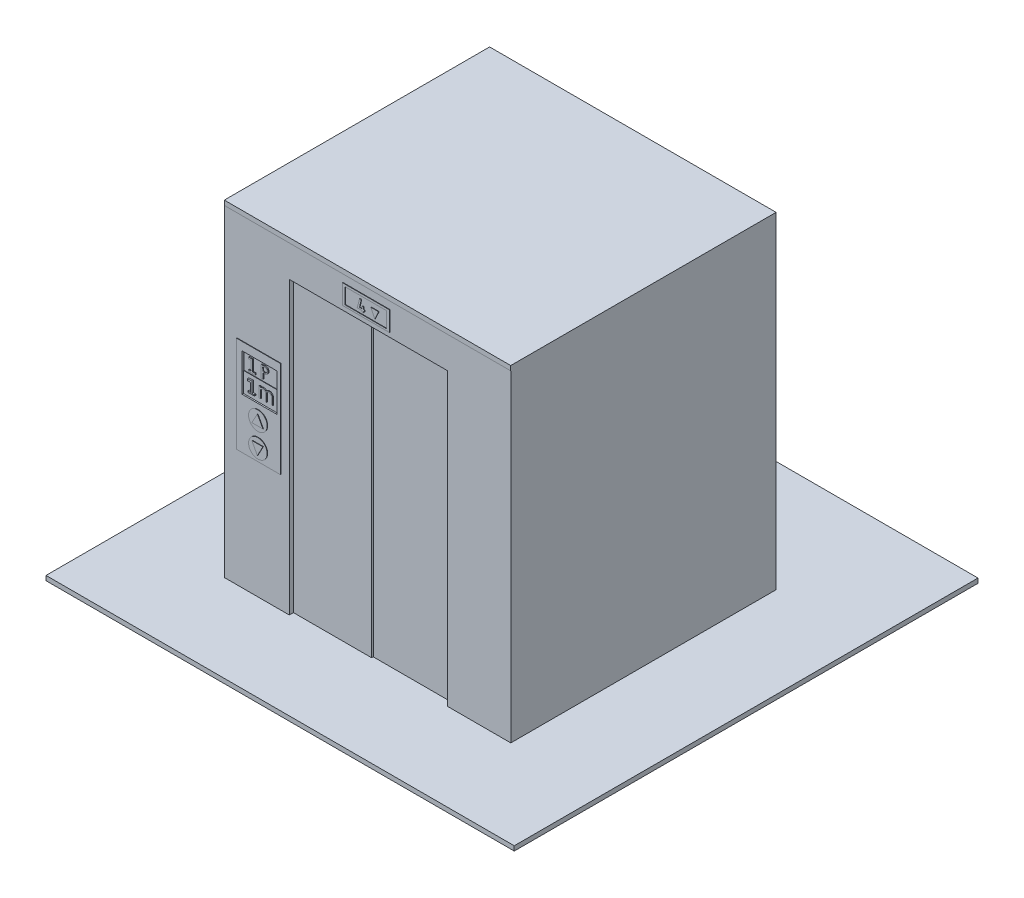
SolidWorks part; units mm, degrees
ref_plane "Front Plane" through (0, 0, 0) normal (0, 0, 1) x (1, 0, 0)
ref_plane "Top Plane" through (0, 0, 0) normal (0, 1, 0) x (1, 0, 0)
ref_plane "Right Plane" through (0, 0, 0) normal (1, 0, 0) x (0, 0, -1)
sketch "Sketch1" plane through (0, 0, 0) normal (0, 1, 0) x (1, 0, 0)
  line L1 (-508.5752, 503.6902) -> (508.5752, 503.6902)
  line L2 (-508.5752, 503.6902) -> (-508.5752, -503.6902)
  line L3 (-508.5752, -503.6902) -> (508.5752, -503.6902)
  line L4 (508.5752, 503.6902) -> (508.5752, -503.6902)
  line L5 (-508.5752, 503.6902) -> (508.5752, -503.6902) construction
  line L6 (-508.5752, -503.6902) -> (508.5752, 503.6902) construction
  point P0 (0, 0)
extrude "Boss-Extrude1" add sketch "Sketch1" along normal blind 10
sketch "Sketch2" plane through (0, 10, 0) normal (0, 1, 0) x (1, 0, 0)
  line L1 (-310.9875, 262.3228) -> (311.3377, 262.3228)
  line L2 (-310.9875, 262.3228) -> (-310.9875, -313.9536)
  line L3 (-310.9875, -313.9536) -> (311.3377, -313.9536)
  line L4 (311.3377, 262.3228) -> (311.3377, -313.9536)
  line L5 (-272.0145, 218.0111) -> (278.8911, 218.0111)
  line L6 (-272.0145, 218.0111) -> (-272.0145, -277.642)
  line L7 (-272.0145, -277.642) -> (278.8911, -277.642)
  line L8 (278.8911, 218.0111) -> (278.8911, -277.642)
extrude "Boss-Extrude2" add sketch "Sketch2" along normal blind 700
sketch "Sketch3" plane through (0, 710, 0) normal (0, 1, 0) x (1, 0, 0)
  line L1 (-310.9875, 262.3228) -> (311.3377, 262.3228)
  line L2 (-310.9875, 262.3228) -> (-310.9875, -313.9536)
  line L3 (-310.9875, -313.9536) -> (311.3377, -314.1051)
  line L4 (311.3377, 262.3228) -> (311.3377, -314.1051)
  point P4 (-310.9875, 262.3228)
  point P5 (-311.772, -314.1051)
  point P6 (-310.9875, -313.9536)
extrude "Boss-Extrude3" add sketch "Sketch3" along normal blind 10
sketch "Sketch4" plane through (0, 0, 313.9536) normal (0, 0, 1) x (1, 0, 0)
  line L1 (-169.9016, 641.4575) -> (173.8441, 641.4575)
  line L2 (-169.9016, 641.4575) -> (-169.9016, 10)
  line L3 (-169.9016, 10) -> (173.8441, 10)
  line L4 (173.8441, 641.4575) -> (173.8441, 10)
extrude "Cut-Extrude1" cut sketch "Sketch4" against normal blind 40
sketch "Sketch5" plane through (0, 0, 313.9536) normal (0, 0, 1) x (1, 0, 0)
  line L1 (-283.6713, 474.5331) -> (-187.5856, 474.5331)
  line L2 (-283.6713, 474.5331) -> (-283.6713, 265.4455)
  line L3 (-283.6713, 265.4455) -> (-187.5856, 265.4455)
  line L4 (-187.5856, 474.5331) -> (-187.5856, 265.4455)
extrude "Boss-Extrude4" add sketch "Sketch5" along normal blind 1
sketch "Sketch6" plane through (0, 0, 314.9536) normal (0, 0, 1) x (1, 0, 0)
  line L1 (-271.1746, 418.75) -> (-195.647, 418.75)
  line L2 (-271.1746, 418.75) -> (-271.1746, 375.0617)
  line L3 (-271.1746, 375.0617) -> (-195.647, 375.0617)
  line L4 (-195.647, 418.75) -> (-195.647, 375.0617)
extrude "Cut-Extrude2" cut sketch "Sketch6" against normal blind 1
sketch "Sketch7" plane through (0, 0, 314.9536) normal (0, 0, 1) x (1, 0, 0)
  circle A0 centre (-236.0757, 343.6172) radius 20.2971
  circle A1 centre (-236.0757, 291.5015) radius 20.232
extrude "Boss-Extrude5" add sketch "Sketch7" along normal blind 1
sketch "Sketch8" plane through (0, 0, 315.9536) normal (0, 0, 1) x (1, 0, 0)
  line L0 (-248.1005, 334.3432) -> (-224.1168, 334.3432)
  line L1 (-224.1168, 334.3432) -> (-236.1087, 356.5701)
  line L2 (-236.1087, 356.5701) -> (-248.1005, 334.3432)
  line L3 (-248.1005, 300.7341) -> (-224.1168, 300.7341)
  line L4 (-224.1168, 300.7341) -> (-236.1087, 278.0211)
  line L5 (-236.1087, 278.0211) -> (-248.1005, 300.7341)
extrude "Boss-Extrude6" add sketch "Sketch8" along normal blind 1
sketch "Sketch9" plane through (-169.9016, 0, 0) normal (1, 0, 0) x (0, 0, -1)
  line L1 (-304.9322, 641.4575) -> (-277.642, 641.4575)
  line L2 (-304.9322, 641.4575) -> (-304.9322, 10)
  line L3 (-304.9322, 10) -> (-277.642, 10)
  line L4 (-277.642, 641.4575) -> (-277.642, 10)
extrude "Boss-Extrude7" add sketch "Sketch9" along normal blind 170
sketch "Sketch10" plane through (0.0984, 0, 0) normal (1, 0, 0) x (0, 0, -1)
  line L1 (-301.4683, 640.5034) -> (-277.642, 640.5034)
  line L2 (-301.4683, 640.5034) -> (-301.4683, 10)
  line L3 (-301.4683, 10) -> (-277.642, 10)
  line L4 (-277.642, 640.5034) -> (-277.642, 10)
extrude "Boss-Extrude8" add sketch "Sketch10" along normal blind 170
sketch "Sketch11" plane through (0, 0, 313.9536) normal (0, 0, 1) x (1, 0, 0)
  line L1 (-53.7077, 693.9278) -> (48.7244, 693.9278)
  line L2 (-53.7077, 693.9278) -> (-53.7077, 651.2448)
  line L3 (-53.7077, 651.2448) -> (48.7244, 651.2448)
  line L4 (48.7244, 693.9278) -> (48.7244, 651.2448)
extrude "Boss-Extrude9" add sketch "Sketch11" along normal blind 1
sketch "Sketch12" plane through (0, 0, 314.9536) normal (0, 0, 1) x (1, 0, 0)
  line L1 (-47.5467, 689.1219) -> (41.8868, 689.1219)
  line L2 (-47.5467, 689.1219) -> (-47.5467, 655.2159)
  line L3 (-47.5467, 655.2159) -> (41.8868, 655.2159)
  line L4 (41.8868, 689.1219) -> (41.8868, 655.2159)
extrude "Cut-Extrude3" cut sketch "Sketch12" against normal blind 1
sketch "Sketch13" plane through (0, 0, 313.9536) normal (0, 0, 1) x (1, 0, 0)
  line L0 (-16.1887, 682.3335) -> (-12.3636, 682.3335)
  line L1 (-12.3636, 682.3335) -> (-16.2809, 666.1802)
  line L2 (-16.2809, 666.1802) -> (-10.8261, 666.1802)
  line L3 (-5.3714, 666.1802) -> (-5.3714, 662.7972)
  line L4 (-5.3714, 662.7972) -> (-7.9099, 662.7972)
  line L5 (-21.2894, 662.7972) -> (-16.1887, 682.3335)
  line L6 (-10.8261, 671.5233) -> (-10.8261, 666.1802)
  line L7 (-10.8261, 659.937) -> (-7.9099, 659.937)
  line L8 (-7.9099, 659.937) -> (-7.9099, 662.7972)
  line L9 (-7.9099, 671.5233) -> (-10.8261, 671.5233)
  line L10 (-10.8261, 662.7972) -> (-10.8261, 659.937)
  line L11 (-7.9099, 666.1802) -> (-5.3714, 666.1802)
  line L12 (-7.9099, 666.1802) -> (-7.9099, 671.5233)
  line L13 (-10.8261, 662.7972) -> (-21.2894, 662.7972)
  point P14 (-12.3636, 682.3335)
extrude "Boss-Extrude10" add sketch "Sketch13" along normal blind 1
sketch "Sketch14" plane through (0, 0, 313.9536) normal (0, 0, 1) x (1, 0, 0)
  line L0 (8.2825, 678.5261) -> (25.4536, 678.5261)
  line L1 (25.4536, 678.5261) -> (16.868, 660.4022)
  line L2 (16.868, 660.4022) -> (8.2825, 678.5261)
extrude "Boss-Extrude11" add sketch "Sketch14" along normal blind 1
sketch "Sketch15" plane through (0, 0, 313.9536) normal (0, 0, 1) x (1, 0, 0)
  line L0 (-253.3924, 406.4083) -> (-253.3924, 387.5651)
  line L1 (-253.3924, 387.5651) -> (-258.9323, 387.5651)
  line L2 (-258.9323, 387.5651) -> (-258.9323, 385.0304)
  line L3 (-258.9323, 385.0304) -> (-244.3761, 385.0304)
  line L4 (-244.3761, 385.0304) -> (-244.3761, 387.5681)
  line L5 (-244.3761, 387.5681) -> (-249.8802, 387.5681)
  line L6 (-249.8802, 387.5681) -> (-249.8802, 410.5631)
  line L7 (-249.8802, 410.5631) -> (-259.6929, 410.2522)
  line L8 (-259.6929, 410.2522) -> (-259.5666, 406.4083)
  line L9 (-259.5666, 406.4083) -> (-253.3924, 406.4083)
  point P2 (-258.3834, 404.7993)
  point P11 (-259.9453, 407.8787)
  point P12 (-253.3924, 406.4083)
  point P13 (-259.9952, 408.7496)
  point P14 (-258.6093, 405.0526)
  point P15 (-259.9442, 411.2226)
  point P16 (-259.5666, 406.4083)
  point P17 (-260.0212, 411.7176)
  point P18 (-259.6929, 410.2522)
extrude "Boss-Extrude12" add sketch "Sketch15" along normal blind 1
sketch "Sketch16" plane through (0, 0, 313.9536) normal (0, 0, 1) x (1, 0, 0)
  line L0 (-235.6485, 408.4658) -> (-235.6485, 385.5858)
  line L1 (-235.6485, 385.5858) -> (-232.1063, 385.5858)
  line L2 (-232.1063, 385.5858) -> (-232.2231, 401.9914)
  line L3 (-235.6485, 408.4658) -> (-231.8951, 408.4658)
  line L4 (-231.8951, 408.4658) -> (-231.8951, 406.5499)
  line L5 (-221.9834, 403.0568) -> (-221.9834, 385.5858)
  line L6 (-221.9834, 385.5858) -> (-218.8212, 385.5858)
  line L7 (-218.8212, 385.5858) -> (-219.0863, 397.9701)
  line L8 (-208.8863, 401.5917) -> (-208.8863, 385.5858)
  line L9 (-208.8863, 385.5858) -> (-206.271, 385.5858)
  line L10 (-206.271, 385.5858) -> (-206.5126, 401.9271)
  line L11 (-219.2828, 403.1887) -> (-219.0863, 397.9701)
  arc A4 (-221.9834, 403.0568) -> (-232.2231, 401.9914) centre (-226.8379, 399.9737) ccw
  arc A6 (-208.8863, 401.5917) -> (-219.2828, 403.1887) centre (-214.4049, 400.3049) ccw
  arc A7 (-206.5126, 401.9271) -> (-220.6047, 405.4509) centre (-214.4049, 400.3049) ccw
  arc A8 (-220.6047, 405.4509) -> (-231.8951, 406.6078) centre (-226.8379, 400.2912) ccw
  point P9 (-206.271, 385.5858)
  point P11 (-208.8863, 385.5858)
  point P13 (-208.8863, 401.5917)
  line M5 (-271.1746, 418.75) -> (-271.1746, 375.0617)
  line M6 (-271.1746, 375.0617) -> (-195.647, 375.0617)
  line M7 (-195.647, 375.0617) -> (-195.647, 418.75)
  line M8 (-195.647, 418.75) -> (-271.1746, 418.75)
  line M9 (-253.3924, 387.5651) -> (-253.3924, 406.4083)
  line M10 (-253.3924, 406.4083) -> (-259.5666, 406.4083)
  line M11 (-259.5666, 406.4083) -> (-259.6929, 410.2522)
  line M12 (-259.6929, 410.2522) -> (-249.8802, 410.5631)
  line M13 (-249.8802, 410.5631) -> (-249.8802, 387.5681)
  line M14 (-249.8802, 387.5681) -> (-244.3761, 387.5681)
  line M15 (-244.3761, 387.5681) -> (-244.3761, 385.0304)
  line M16 (-244.3761, 385.0304) -> (-258.9323, 385.0304)
  line M17 (-258.9323, 385.0304) -> (-258.9323, 387.5651)
  line M18 (-258.9323, 387.5651) -> (-253.3924, 387.5651)
extrude "Cut-Extrude4" cut sketch "Sketch16" against normal blind 2 contours A8 A7 L10 L9 L8 A6 L11 L7 L6 L5 A4 L2 L1 L0 L3 L4 M8 M5 M6 M7 M18 M9 M10 M11 M12 M13 M14 M15 M16 M17
sketch "Sketch17" plane through (0, 0, 311.9536) normal (0, 0, 1) x (1, 0, 0)
  line L1 (-271.2094, 458.8572) -> (-195.647, 458.8572)
  line L2 (-271.2094, 458.8572) -> (-271.2094, 418.4414)
  line L3 (-271.2094, 418.4414) -> (-195.7041, 418.4414)
  line L4 (-195.647, 458.8572) -> (-195.7041, 418.4414)
  point P4 (-271.2094, 418.4414)
  point P5 (-271.2094, 458.8572)
  point P6 (-195.7041, 418.4414)
extrude "Cut-Extrude5" cut sketch "Sketch17" against normal blind 1
sketch "Sketch18" plane through (0, 0, 314.9536) normal (0, 0, 1) x (1, 0, 0)
  line L1 (-271.1417, 456.7599) -> (-195.647, 456.7599)
  line L2 (-271.1417, 456.7599) -> (-271.1417, 418.75)
  line L3 (-271.1417, 418.75) -> (-195.647, 418.75)
  line L4 (-195.647, 456.7599) -> (-195.647, 418.75)
extrude "Cut-Extrude6" cut sketch "Sketch18" against normal blind 3
sketch "Sketch19" plane through (0, 0, 310.9536) normal (0, 0, 1) x (1, 0, 0)
  line L0 (-254.3129, 446.7406) -> (-254.3129, 426.3557)
  line L1 (-254.3129, 426.3557) -> (-259.3962, 426.3557)
  line L2 (-259.3962, 426.3557) -> (-259.3962, 423.275)
  line L3 (-259.3962, 423.275) -> (-244.6783, 423.275)
  line L4 (-244.6783, 423.275) -> (-244.6783, 426.3453)
  line L5 (-244.6783, 426.3453) -> (-250.7281, 426.3453)
  line L6 (-250.7281, 426.3453) -> (-250.7281, 450.1154)
  line L7 (-250.7281, 450.1154) -> (-259.3962, 450.1154)
  line L8 (-259.3962, 450.1154) -> (-259.3962, 446.7406)
  line L9 (-259.3962, 446.7406) -> (-254.3129, 446.7406)
extrude "Boss-Extrude14" add sketch "Sketch19" along normal blind 2
sketch "Sketch20" plane through (0, 0, 310.9536) normal (0, 0, 1) x (1, 0, 0)
  line L0 (-231.7389, 449.8367) -> (-231.7389, 423.3615)
  line L1 (-231.7389, 423.3615) -> (-228.298, 423.3615)
  line L2 (-228.298, 423.3615) -> (-228.1456, 436.3278)
  line L3 (-231.7389, 449.8367) -> (-231.7389, 450.2937)
  line L4 (-231.7389, 450.2937) -> (-228.6156, 450.2937)
  line L5 (-228.6156, 450.2937) -> (-228.5661, 449.4447)
  line L6 (-228.5661, 446.4929) -> (-228.298, 439.2366)
  arc A0 (-228.1456, 436.3278) -> (-228.5661, 449.4447) centre (-224.524, 443.0091) ccw
  arc A1 (-228.298, 439.2366) -> (-228.5661, 446.4929) centre (-224.524, 443.0091) ccw
  point P5 (-228.298, 439.2366)
extrude "Boss-Extrude15" add sketch "Sketch20" along normal blind 2
